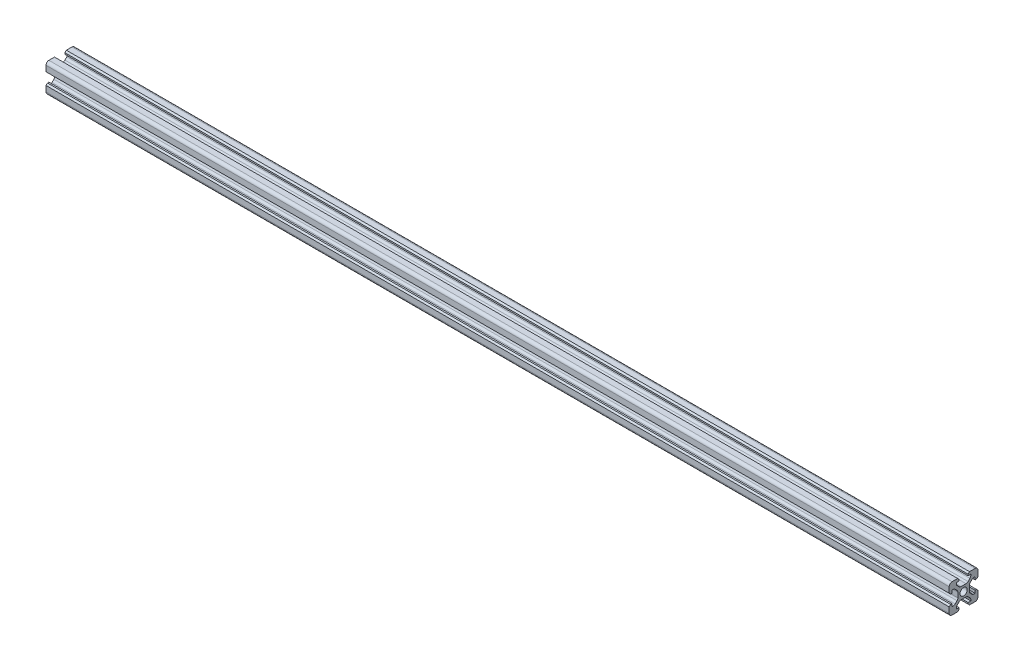
SolidWorks part; units mm, degrees
ref_plane "Front Plane" through (0, 0, 0) normal (0, 0, 1) x (1, 0, 0)
ref_plane "Top Plane" through (0, 0, 0) normal (0, 1, 0) x (1, 0, 0)
ref_plane "Right Plane" through (0, 0, 0) normal (1, 0, 0) x (0, 0, -1)
sketch "Sketch1" plane through (0, 0, 0) normal (1, 0, 0) x (0, 0, -1)
  line B0 (-4.1, 10) -> (-8, 10)
  line B1 (-3.1, 8) -> (-3.1, 9)
  line B2 (9, -3.1) -> (10, -4.1)
  line B3 (3.1, 8) -> (3.1, 9)
  line B4 (4.4142, 5.8284) -> (3.1236, 4.5379)
  line B5 (10, 4.1) -> (9, 3.1)
  line B6 (5, 8) -> (3.1, 8)
  line B7 (5, 7.2426) -> (5, 8)
  line B8 (-3.1, 8) -> (-5, 8)
  line B9 (-5, 7.2426) -> (-5, 8)
  line B10 (4.1, 10) -> (3.1, 9)
  line B11 (5.8284, -4.4142) -> (4.5379, -3.1236)
  line B12 (7.2426, -5) -> (8, -5)
  line B13 (8, -3.1) -> (8, -5)
  line B14 (7.2426, 5) -> (8, 5)
  line B15 (8, 10) -> (4.1, 10)
  line B16 (-1.7094, 3.9521) -> (1.7094, 3.9521)
  line B17 (8, 5) -> (8, 3.1)
  line B18 (8, 3.1) -> (9, 3.1)
  line B19 (-3.1, 9) -> (-4.1, 10)
  line B20 (8, -3.1) -> (9, -3.1)
  line B21 (3.9521, 1.7094) -> (3.9521, -1.7094)
  line B22 (-3.1236, 4.5379) -> (-4.4142, 5.8284)
  line B23 (10, -4.1) -> (10, -8)
  line B24 (4.5379, 3.1236) -> (5.8284, 4.4142)
  line B25 (-3.1, -9) -> (-4.1, -10)
  line B26 (8, -10) -> (4.1, -10)
  line B27 (4.1, -10) -> (3.1, -9)
  line B28 (-4.4142, -5.8284) -> (-3.1236, -4.5379)
  line B29 (-5, -7.2426) -> (-5, -8)
  line B30 (-3.1, -8) -> (-5, -8)
  line B31 (5, -7.2426) -> (5, -8)
  line B32 (5, -8) -> (3.1, -8)
  line B33 (3.1, -8) -> (3.1, -9)
  line B34 (-3.1, -8) -> (-3.1, -9)
  line B35 (1.7094, -3.9521) -> (-1.7094, -3.9521)
  line B36 (-4.1, -10) -> (-8, -10)
  line B37 (3.1236, -4.5379) -> (4.4142, -5.8284)
  line B38 (-9, 3.1) -> (-10, 4.1)
  line B39 (-10, -8) -> (-10, -4.1)
  line B40 (-10, -4.1) -> (-9, -3.1)
  line B41 (-5.8284, 4.4142) -> (-4.5379, 3.1236)
  line B42 (-7.2426, 5) -> (-8, 5)
  line B43 (-8, 3.1) -> (-8, 5)
  line B44 (-7.2426, -5) -> (-8, -5)
  line B45 (-8, -5) -> (-8, -3.1)
  line B46 (-8, -3.1) -> (-9, -3.1)
  line B47 (-8, 3.1) -> (-9, 3.1)
  line B48 (-3.9521, -1.7094) -> (-3.9521, 1.7094)
  line B49 (-10, 8) -> (-10, 4.1)
  line B50 (-4.5379, -3.1236) -> (-5.8284, -4.4142)
  line B51 (10, 8) -> (10, 4.1)
  circle B52 centre (0, 0) radius 2.5
  arc B53 (-4.5379, 3.1236) -> (-3.9521, 1.7094) centre (-5.9521, 1.7094) cw
  arc B54 (-5.8284, 4.4142) -> (-7.2426, 5) centre (-7.2426, 3) ccw
  arc B55 (-5, 7.2426) -> (-4.4142, 5.8284) centre (-3, 7.2426) ccw
  arc B56 (5, 7.2426) -> (4.4142, 5.8284) centre (3, 7.2426) cw
  arc B57 (7.2426, 5) -> (5.8284, 4.4142) centre (7.2426, 3) ccw
  arc B58 (5.8284, -4.4142) -> (7.2426, -5) centre (7.2426, -3) ccw
  arc B59 (5, -7.2426) -> (4.4142, -5.8284) centre (3, -7.2426) ccw
  arc B60 (-4.4142, -5.8284) -> (-5, -7.2426) centre (-3, -7.2426) ccw
  arc B61 (-7.2426, -5) -> (-5.8284, -4.4142) centre (-7.2426, -3) ccw
  arc B62 (-3.9521, -1.7094) -> (-4.5379, -3.1236) centre (-5.9521, -1.7094) cw
  arc B63 (-3.1236, -4.5379) -> (-1.7094, -3.9521) centre (-1.7094, -5.9521) cw
  arc B64 (1.7094, -3.9521) -> (3.1236, -4.5379) centre (1.7094, -5.9521) cw
  arc B65 (4.5379, -3.1236) -> (3.9521, -1.7094) centre (5.9521, -1.7094) cw
  arc B66 (3.9521, 1.7094) -> (4.5379, 3.1236) centre (5.9521, 1.7094) cw
  arc B67 (1.7094, 3.9521) -> (3.1236, 4.5379) centre (1.7094, 5.9521) ccw
  arc B68 (-1.7094, 3.9521) -> (-3.1236, 4.5379) centre (-1.7094, 5.9521) cw
  arc B69 (10, 8) -> (8, 10) centre (8, 8) ccw
  arc B70 (-8, -10) -> (-10, -8) centre (-8, -8) cw
  arc B71 (10, -8) -> (8, -10) centre (8, -8) cw
  arc B72 (-8, 10) -> (-10, 8) centre (-8, 8) ccw
sketch_block_instance "2020-1"
sketch_block "2020" parameters "D1"=2
extrude "Boss-Extrude1" add sketch "Sketch1" along normal blind 626
